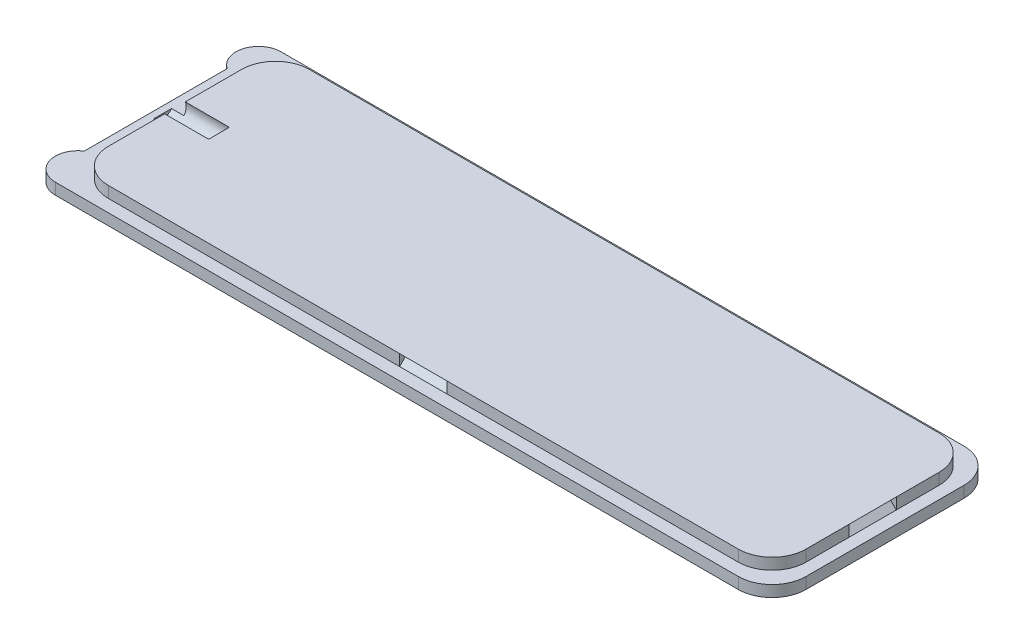
SolidWorks part; units mm, degrees
material "ABS"
ref_plane "Front Plane" through (0, 0, 0) normal (0, 0, 1) x (1, 0, 0)
ref_plane "Top Plane" through (0, 0, 0) normal (0, 1, 0) x (1, 0, 0)
ref_plane "Right Plane" through (0, 0, 0) normal (1, 0, 0) x (0, 0, -1)
ref_plane "Plane1" through (160, 0, 0) normal (1, 0, 0) x (0, 0, -1)
ref_plane "Plane2" through (314, 0, 0) normal (1, 0, 0) x (0, 0, -1)
ref_plane "Plane3" through (0, 0, -50) normal (0, 0, 1) x (1, 0, 0)
sketch "Sketch8" plane through (0, 0, 0) normal (0, 1, 0) x (1, 0, 0)
  line L1 (15, 0) -> (305, 0)
  line L2 (0, 15) -> (0, 85)
  line L3 (15, 100) -> (305, 100)
  line L4 (320, 15) -> (320, 85)
  arc A0 (305, 100) -> (320, 85) centre (305, 85) cw
  arc A1 (320, 15) -> (305, 0) centre (305, 15) cw
  arc A2 (15, 0) -> (0, 15) centre (15, 15) cw
  arc A3 (0, 85) -> (15, 100) centre (15, 85) cw
  point P11 (0, 0)
  dimension "D1" = 15
extrude "Boss-Extrude1" add sketch "Sketch8" along normal blind 10
ref_plane "Plane4" through (0, 10, 0) normal (0, 1, 0) x (1, 0, 0)
sketch "Sketch9" plane through (0, 10, 0) normal (0, 1, 0) x (1, 0, 0)
  line L1 (15, 0) -> (305, 0)
  line L2 (0, 15) -> (0, 85)
  line L3 (15, 100) -> (305, 100)
  line L4 (320, 15) -> (320, 85)
  line L13 (20.5, 94.5) -> (299.5, 94.5)
  line L14 (5.5, 79.5) -> (5.5, 20.5)
  line L15 (20.5, 5.5) -> (299.5, 5.5)
  line L16 (314.5, 79.5) -> (314.5, 20.5)
  arc A4 (305, 100) -> (320, 85) centre (305, 85) cw
  arc A5 (320, 15) -> (305, 0) centre (305, 15) cw
  arc A6 (15, 0) -> (0, 15) centre (15, 15) cw
  arc A7 (0, 85) -> (15, 100) centre (15, 85) cw
  arc A12 (299.5, 94.5) -> (314.5, 79.5) centre (299.5, 79.5) cw
  arc A13 (314.5, 20.5) -> (299.5, 5.5) centre (299.5, 20.5) cw
  arc A14 (20.5, 5.5) -> (5.5, 20.5) centre (20.5, 20.5) cw
  arc A15 (5.5, 79.5) -> (20.5, 94.5) centre (20.5, 79.5) cw
  point P23 (0, 0)
  dimension "D1" = 15
  dimension "D2" = 15
extrude "Cut-Extrude7" cut sketch "Sketch9" against normal blind 5
sketch "Sketch11" plane through (160, 0, 0) normal (1, 0, 0) x (0, 0, -1)
  line L13 (5.5, 10) -> (5.5, 5)
  line L14 (5.5, 5) -> (8, 7.5)
  line L15 (8, 7.5) -> (5.5, 10)
  line L16 (94.5, 10) -> (94.5, 5)
  line L17 (94.5, 5) -> (92, 7.5)
  line L18 (92, 7.5) -> (94.5, 10)
extrude "Cut-Extrude8" cut sketch "Sketch11" against normal blind 10.5 and the other way blind 10.5
sketch "Sketch13" plane through (0, 0, -50) normal (0, 0, 1) x (1, 0, 0)
  line L6 (314.5, 5) -> (314.5, 10)
  line L7 (314.5, 10) -> (312, 7.5)
  line L8 (312, 7.5) -> (314.5, 5)
extrude "Cut-Extrude9" cut sketch "Sketch13" against normal blind 10.5 and the other way blind 10.5
sketch "Sketch14" plane through (0, 0, 0) normal (1, 0, 0) x (0, 0, -1)
  line L0 (50, 0) -> (50, 8)
  line L1 (85, 0) -> (15, 0) construction
  circle A0 centre (50, 8) radius 5
extrude "Cut-Extrude10" cut sketch "Sketch14" along normal blind 25
sketch "Sketch15" plane through (0, 0, 0) normal (0, 1, 0) x (1, 0, 0)
  line L2 (-7.5, 100) -> (-7.5, 0)
  line L6 (0, 15) -> (0, 85)
  line L7 (15, 100) -> (-7.5, 100)
  line L8 (15, 0) -> (-7.5, 0)
  arc A0 (15, 0) -> (0, 15) centre (15, 15) cw
  arc A1 (15, 100) -> (0, 85) centre (15, 85) ccw
  point P16 (0, 0)
  dimension "D1" = 15
extrude "Boss-Extrude2" add sketch "Sketch15" along normal blind 5
sketch "Sketch16" plane through (0, 0, 0) normal (0, 1, 0) x (1, 0, 0)
  line L0 (2.5, 100) -> (-7.5, 100)
  line L2 (-3, 50) -> (-3, 18.3516)
  line L3 (-3, 50) -> (-3, 81.6484)
  line L4 (2.5, 0) -> (-7.5, 0)
  line L5 (-7.5, 0) -> (-7.5, 10)
  line L6 (-7.5, 10) -> (-7.5, 90)
  line L7 (2.5, 100) -> (-7.5, 100)
  line L8 (-7.5, 90) -> (-7.5, 10)
  line L9 (-7.5, 90) -> (-7.5, 100)
  line L10 (2.5, 0) -> (-7.5, 0)
  line L11 (-7.5, 0) -> (-7.5, 10)
  arc A0 (-7.5, 90) -> (2.5, 100) centre (2.5, 90) cw
  arc A1 (2.5, 0) -> (-7.5, 10) centre (2.5, 10) cw
  arc A2 (-7.5, 90) -> (2.5, 80) centre (2.5, 90) ccw
  arc A3 (-7.5, 10) -> (2.5, 20) centre (2.5, 10) cw
  point P10 (-7.5, 100)
  point P13 (-7.5, 0)
  dimension "D1" = 10
extrude "Cut-Extrude12" cut sketch "Sketch16" along normal blind 5 contours L4 A1 L5 | L6 A3 L2 L3 A2 | L9 A0 L0
